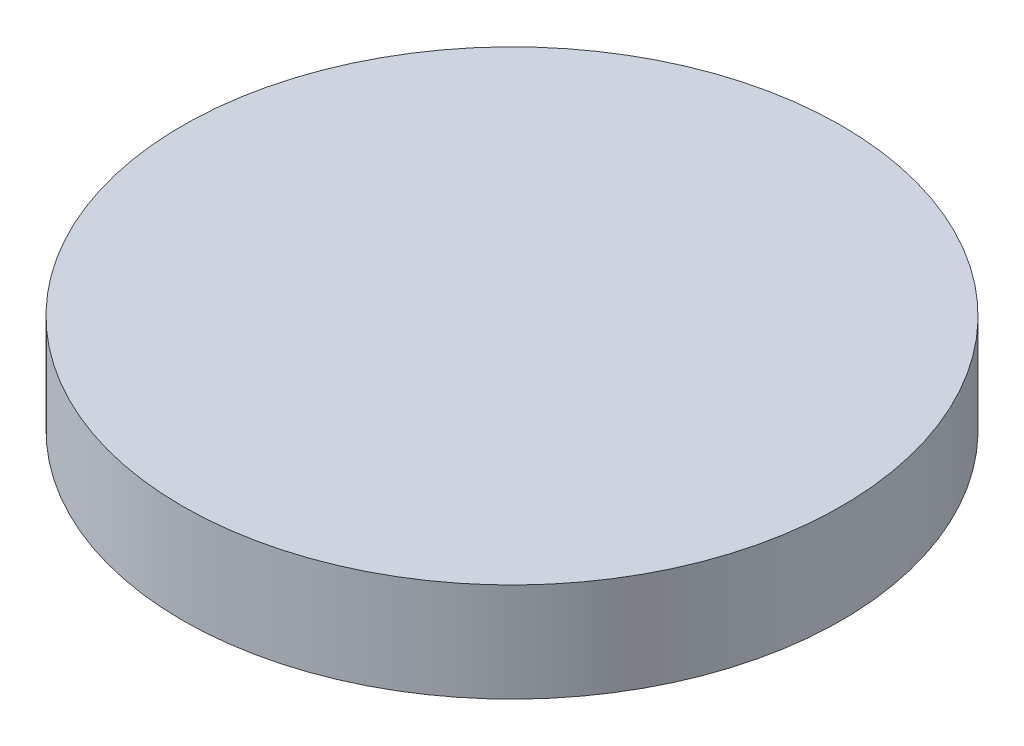
SolidWorks part; units mm, degrees
material "Poplar plywood painted"
ref_plane "Front Plane" through (0, 0, 0) normal (0, 0, 1) x (1, 0, 0)
ref_plane "Top Plane" through (0, 0, 0) normal (0, 1, 0) x (1, 0, 0)
ref_plane "Right Plane" through (0, 0, 0) normal (1, 0, 0) x (0, 0, -1)
sketch "Sketch1" plane through (0, 0, 0) normal (0, 1, 0) x (1, 0, 0)
  circle A0 centre (0, 0) radius 60
  dimension "D1" = 120
extrude "Boss-Extrude1" add sketch "Sketch1" along normal blind 18
